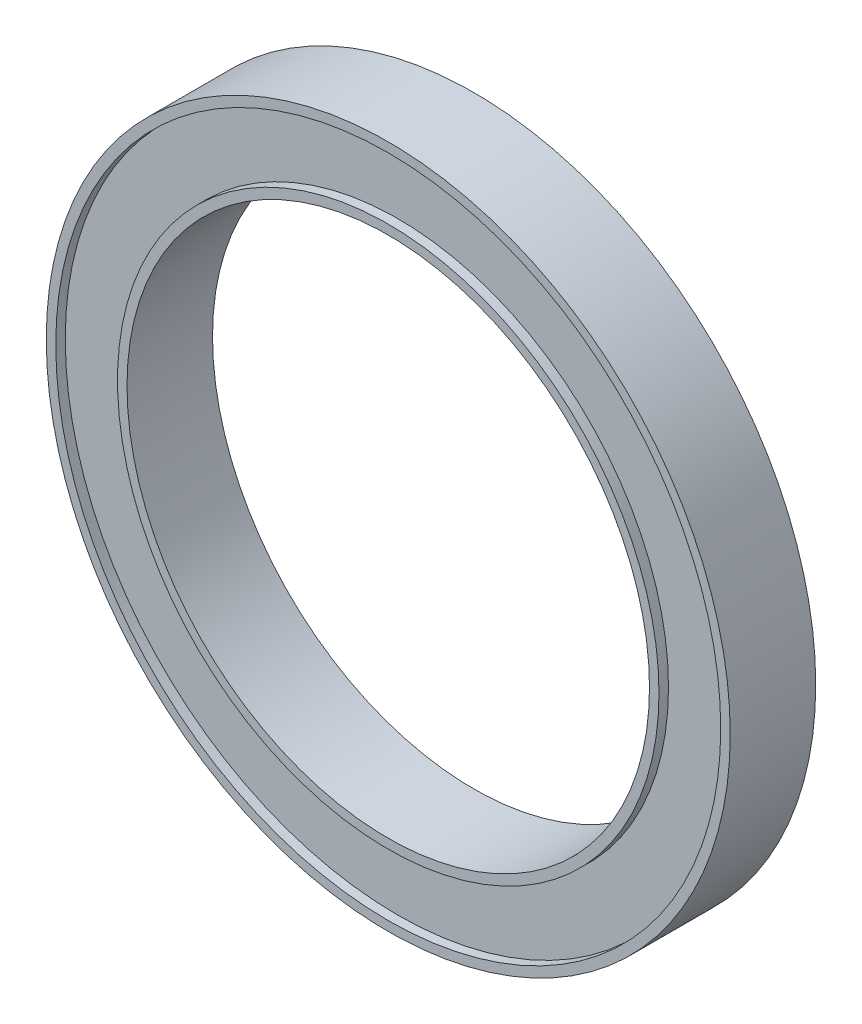
SolidWorks part; units mm, degrees
ref_plane "前视基准面" through (0, 0, 0) normal (0, 0, 1) x (1, 0, 0)
ref_plane "上视基准面" through (0, 0, 0) normal (0, 1, 0) x (1, 0, 0)
ref_plane "右视基准面" through (0, 0, 0) normal (1, 0, 0) x (0, 0, -1)
sketch "草图1" plane through (0, 0, 0) normal (0, 0, 1) x (1, 0, 0)
  circle A0 centre (0, 0) radius 36
  dimension "D1" = 72
extrude "凸台-拉伸1" add sketch "草图1" along normal blind 9
sketch "草图2" plane through (0, 0, 9) normal (0, 0, 1) x (1, 0, 0)
  circle A0 centre (0, 0) radius 27.5
  dimension "D1" = 55
extrude "切除-拉伸1" cut sketch "草图2" against normal through all
sketch "草图3" plane through (0, 0, 9) normal (0, 0, 1) x (1, 0, 0)
  circle A0 centre (0, 0) radius 28.5
  circle A1 centre (0, 0) radius 35
  dimension "D1" = 57
  dimension "D2" = 70
extrude "切除-拉伸2" cut sketch "草图3" against normal blind 1
sketch "草图4" plane through (0, 0, 0) normal (0, 0, -1) x (-1, 0, 0)
  circle A0 centre (0, 0) radius 28.5
  circle A1 centre (0, 0) radius 35
  dimension "D1" = 57
  dimension "D2" = 70
extrude "切除-拉伸3" cut sketch "草图4" against normal blind 1
